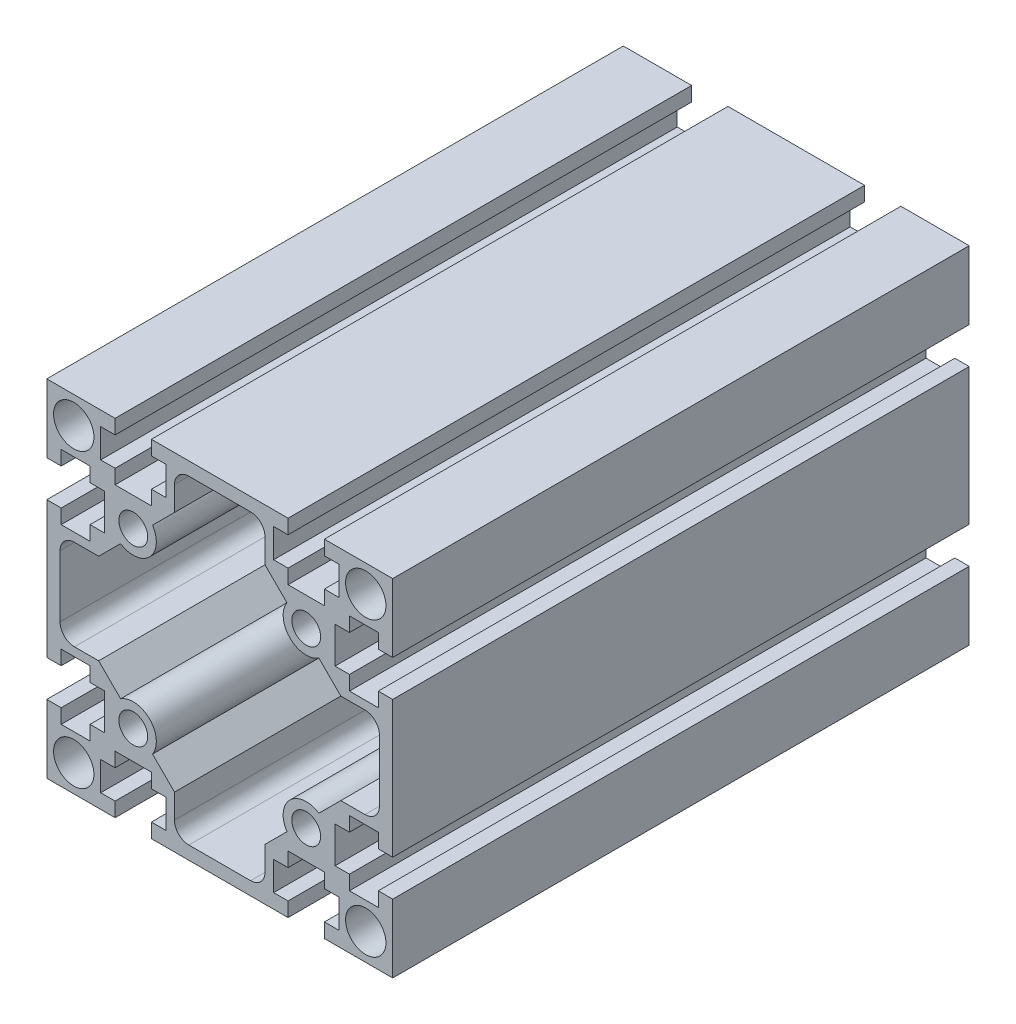
SolidWorks part; units mm, degrees
ref_plane "前视基准面" through (0, 0, 0) normal (0, 0, 1) x (1, 0, 0)
ref_plane "上视基准面" through (0, 0, 0) normal (0, 1, 0) x (1, 0, 0)
ref_plane "右视基准面" through (0, 0, 0) normal (1, 0, 0) x (0, 0, -1)
sketch "草图1" plane through (0, 0, 0) normal (0, 0, 1) x (1, 0, 0)
  line L0 (-29.8772, 10.4874) -> (-29.8772, -1.3626)
  line L1 (-19.8772, 16.7874) -> (-19.8772, 10.4874)
  line L2 (0.1228, 28.6374) -> (-11.7272, 28.6374)
  line L3 (0.1228, 26.3374) -> (-5.2272, 26.3374)
  line L4 (-7.7272, 23.8374) -> (-7.7272, 19.6374)
  line L5 (-18.0272, 28.6374) -> (-29.8772, 28.6374)
  line L6 (-29.8772, 28.6374) -> (-29.8772, 16.7874)
  line L7 (-27.3772, 10.4874) -> (-27.3772, 7.9874)
  line L8 (-9.2272, 26.1374) -> (-11.7272, 26.1374)
  line L9 (-22.3772, 10.4874) -> (-22.3772, 7.9874)
  line L10 (-9.2272, 21.1374) -> (-11.7272, 21.1374)
  line L11 (-27.3772, 19.2874) -> (-27.3772, 16.7874)
  line L12 (-22.3772, 19.2874) -> (-22.3772, 16.7874)
  line L13 (-27.3772, 10.4874) -> (-29.8772, 10.4874)
  line L14 (-27.3772, 16.7874) -> (-29.8772, 16.7874)
  line L15 (-27.3772, 19.2874) -> (-22.3772, 19.2874)
  line L16 (-27.3772, 7.9874) -> (-22.3772, 7.9874)
  line L17 (-22.3772, 10.4874) -> (-19.8772, 10.4874)
  line L18 (-22.3772, 16.7874) -> (-19.8772, 16.7874)
  line L19 (-18.0272, 18.6374) -> (-11.7272, 18.6374)
  line L22 (-20.5272, 26.1374) -> (-18.0272, 26.1374)
  line L23 (-20.5272, 21.1374) -> (-18.0272, 21.1374)
  line L24 (-11.7272, 26.1374) -> (-11.7272, 28.6374)
  line L25 (-18.0272, 26.1374) -> (-18.0272, 28.6374)
  line L26 (-20.5272, 26.1374) -> (-20.5272, 21.1374)
  line L27 (-9.2272, 26.1374) -> (-9.2272, 21.1374)
  line L28 (-11.7272, 21.1374) -> (-11.7272, 18.6374)
  line L29 (-18.0272, 21.1374) -> (-18.0272, 18.6374)
  line L30 (30.1228, 10.4874) -> (30.1228, -1.3626)
  line L31 (20.1228, 16.7874) -> (20.1228, 10.4874)
  line L32 (0.1228, 28.6374) -> (11.9728, 28.6374)
  line L33 (0.1228, 26.3374) -> (5.4728, 26.3374)
  line L34 (7.9728, 23.8374) -> (7.9728, 19.6374)
  line L35 (18.2728, 28.6374) -> (30.1228, 28.6374)
  line L36 (30.1228, 28.6374) -> (30.1228, 16.7874)
  line L37 (27.6228, 10.4874) -> (27.6228, 7.9874)
  line L38 (9.4728, 26.1374) -> (11.9728, 26.1374)
  line L39 (22.6228, 10.4874) -> (22.6228, 7.9874)
  line L40 (9.4728, 21.1374) -> (11.9728, 21.1374)
  line L41 (27.6228, 19.2874) -> (27.6228, 16.7874)
  line L42 (22.6228, 19.2874) -> (22.6228, 16.7874)
  line L43 (27.6228, 10.4874) -> (30.1228, 10.4874)
  line L44 (27.6228, 16.7874) -> (30.1228, 16.7874)
  line L45 (27.6228, 19.2874) -> (22.6228, 19.2874)
  line L46 (27.6228, 7.9874) -> (22.6228, 7.9874)
  line L47 (22.6228, 10.4874) -> (20.1228, 10.4874)
  line L48 (22.6228, 16.7874) -> (20.1228, 16.7874)
  line L49 (18.2728, 18.6374) -> (11.9728, 18.6374)
  line L52 (20.7728, 26.1374) -> (18.2728, 26.1374)
  line L53 (20.7728, 21.1374) -> (18.2728, 21.1374)
  line L54 (11.9728, 26.1374) -> (11.9728, 28.6374)
  line L55 (18.2728, 26.1374) -> (18.2728, 28.6374)
  line L56 (20.7728, 26.1374) -> (20.7728, 21.1374)
  line L57 (9.4728, 26.1374) -> (9.4728, 21.1374)
  line L58 (11.9728, 21.1374) -> (11.9728, 18.6374)
  line L59 (18.2728, 21.1374) -> (18.2728, 18.6374)
  line L60 (-29.8772, -13.2126) -> (-29.8772, -1.3626)
  line L61 (-19.8772, -19.5126) -> (-19.8772, -13.2126)
  line L62 (0.1228, -31.3626) -> (-11.7272, -31.3626)
  line L63 (-18.0272, -31.3626) -> (-29.8772, -31.3626)
  line L64 (-29.8772, -31.3626) -> (-29.8772, -19.5126)
  line L65 (-27.3772, -13.2126) -> (-27.3772, -10.7126)
  line L66 (-9.2272, -28.8626) -> (-11.7272, -28.8626)
  line L67 (-22.3772, -13.2126) -> (-22.3772, -10.7126)
  line L68 (-9.2272, -23.8626) -> (-11.7272, -23.8626)
  line L69 (-27.3772, -22.0126) -> (-27.3772, -19.5126)
  line L70 (-22.3772, -22.0126) -> (-22.3772, -19.5126)
  line L71 (-27.3772, -13.2126) -> (-29.8772, -13.2126)
  line L72 (-27.3772, -19.5126) -> (-29.8772, -19.5126)
  line L73 (-27.3772, -22.0126) -> (-22.3772, -22.0126)
  line L74 (-27.3772, -10.7126) -> (-22.3772, -10.7126)
  line L75 (-22.3772, -13.2126) -> (-19.8772, -13.2126)
  line L76 (-22.3772, -19.5126) -> (-19.8772, -19.5126)
  line L77 (-18.0272, -21.3626) -> (-11.7272, -21.3626)
  line L80 (-20.5272, -28.8626) -> (-18.0272, -28.8626)
  line L81 (-20.5272, -23.8626) -> (-18.0272, -23.8626)
  line L82 (-11.7272, -28.8626) -> (-11.7272, -31.3626)
  line L83 (-20.5272, -28.8626) -> (-20.5272, -23.8626)
  line L84 (-9.2272, -28.8626) -> (-9.2272, -23.8626)
  line L85 (-11.7272, -23.8626) -> (-11.7272, -21.3626)
  line L86 (-18.0272, -23.8626) -> (-18.0272, -21.3626)
  line L87 (30.1228, -13.2126) -> (30.1228, -1.3626)
  line L88 (20.1228, -19.5126) -> (20.1228, -13.2126)
  line L89 (0.1228, -31.3626) -> (11.9728, -31.3626)
  line L90 (18.2728, -31.3626) -> (30.1228, -31.3626)
  line L91 (30.1228, -31.3626) -> (30.1228, -19.5126)
  line L92 (27.6228, -13.2126) -> (27.6228, -10.7126)
  line L93 (9.4728, -28.8626) -> (11.9728, -28.8626)
  line L94 (22.6228, -13.2126) -> (22.6228, -10.7126)
  line L95 (9.4728, -23.8626) -> (11.9728, -23.8626)
  line L96 (27.6228, -22.0126) -> (27.6228, -19.5126)
  line L97 (22.6228, -22.0126) -> (22.6228, -19.5126)
  line L98 (27.6228, -13.2126) -> (30.1228, -13.2126)
  line L99 (27.6228, -19.5126) -> (30.1228, -19.5126)
  line L100 (27.6228, -22.0126) -> (22.6228, -22.0126)
  line L101 (27.6228, -10.7126) -> (22.6228, -10.7126)
  line L102 (22.6228, -13.2126) -> (20.1228, -13.2126)
  line L103 (22.6228, -19.5126) -> (20.1228, -19.5126)
  line L104 (18.2728, -21.3626) -> (11.9728, -21.3626)
  line L107 (20.7728, -28.8626) -> (18.2728, -28.8626)
  line L108 (20.7728, -23.8626) -> (18.2728, -23.8626)
  line L109 (11.9728, -28.8626) -> (11.9728, -31.3626)
  line L110 (18.2728, -28.8626) -> (18.2728, -31.3626)
  line L111 (20.7728, -28.8626) -> (20.7728, -23.8626)
  line L112 (9.4728, -28.8626) -> (9.4728, -23.8626)
  line L113 (11.9728, -23.8626) -> (11.9728, -21.3626)
  line L114 (18.2728, -23.8626) -> (18.2728, -21.3626)
  line L115 (-11.5328, 15.8317) -> (-7.7272, 19.6374)
  line L116 (-25.0772, 6.4874) -> (-20.8772, 6.4874)
  line L117 (-17.0716, 10.293) -> (-20.8772, 6.4874)
  line L118 (11.7784, 15.8317) -> (7.9728, 19.6374)
  line L119 (25.3228, 6.4874) -> (21.1228, 6.4874)
  line L120 (17.3172, 10.293) -> (21.1228, 6.4874)
  line L121 (0.1228, -29.0626) -> (-5.2272, -29.0626)
  line L122 (-7.7272, -26.5626) -> (-7.7272, -22.3626)
  line L123 (0.1228, -29.0626) -> (5.4728, -29.0626)
  line L124 (7.9728, -26.5626) -> (7.9728, -22.3626)
  line L125 (-11.5328, -18.557) -> (-7.7272, -22.3626)
  line L126 (-25.0772, -9.2126) -> (-20.8772, -9.2126)
  line L127 (-17.0716, -13.0183) -> (-20.8772, -9.2126)
  line L128 (11.7784, -18.557) -> (7.9728, -22.3626)
  line L129 (25.3228, -9.2126) -> (21.1228, -9.2126)
  line L130 (17.3172, -13.0183) -> (21.1228, -9.2126)
  line L131 (-27.5772, 3.9874) -> (-27.5772, -6.7126)
  line L132 (27.8228, 3.9874) -> (27.8228, -6.7126)
  line L133 (-18.0272, -28.8626) -> (-18.0272, -31.3626)
  arc A0 (-5.2272, 26.3374) -> (-7.7272, 23.8374) centre (-5.2272, 23.8374) ccw
  circle A1 centre (-14.8772, 13.6374) radius 2.5
  arc A2 (-17.0716, 10.293) -> (-11.5328, 15.8317) centre (-14.8772, 13.6374) ccw
  circle A3 centre (-25.2022, 23.9624) radius 3.5
  arc A4 (7.9728, 23.8374) -> (5.4728, 26.3374) centre (5.4728, 23.8374) ccw
  circle A5 centre (15.1228, 13.6374) radius 2.5
  circle A6 centre (25.4478, 23.9624) radius 3.5
  circle A7 centre (-14.8772, -16.3626) radius 2.5
  circle A8 centre (-25.2022, -26.6876) radius 3.5
  circle A9 centre (15.1228, -16.3626) radius 2.5
  circle A10 centre (25.4478, -26.6876) radius 3.5
  arc A11 (11.7784, 15.8317) -> (17.3172, 10.293) centre (15.1228, 13.6374) ccw
  arc A12 (27.8228, 3.9874) -> (25.3228, 6.4874) centre (25.3228, 3.9874) ccw
  arc A13 (-7.7272, -26.5626) -> (-5.2272, -29.0626) centre (-5.2272, -26.5626) ccw
  arc A14 (-11.5328, -18.557) -> (-17.0716, -13.0183) centre (-14.8772, -16.3626) ccw
  arc A15 (5.4728, -29.0626) -> (7.9728, -26.5626) centre (5.4728, -26.5626) ccw
  arc A16 (17.3172, -13.0183) -> (11.7784, -18.557) centre (15.1228, -16.3626) ccw
  arc A17 (-27.5772, -6.7126) -> (-25.0772, -9.2126) centre (-25.0772, -6.7126) ccw
  arc A18 (-25.0772, 6.4874) -> (-27.5772, 3.9874) centre (-25.0772, 3.9874) ccw
  arc A19 (25.3228, -9.2126) -> (27.8228, -6.7126) centre (25.3228, -6.7126) ccw
extrude "凸台-拉伸1" add sketch "草图1" along normal blind 100
